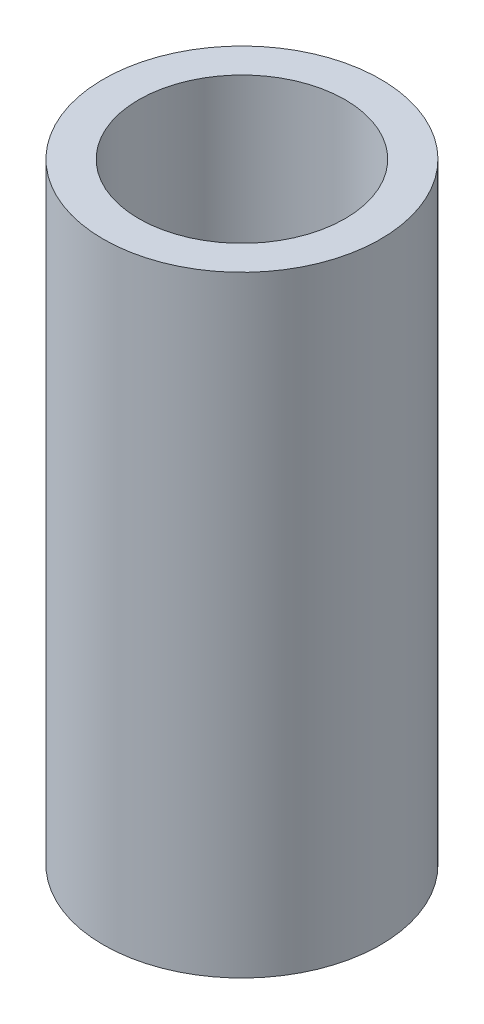
SolidWorks part; units mm, degrees
material "Nylon 101"
ref_plane "Front Plane" through (0, 0, 0) normal (0, 0, 1) x (1, 0, 0)
ref_plane "Top Plane" through (0, 0, 0) normal (0, 1, 0) x (1, 0, 0)
ref_plane "Right Plane" through (0, 0, 0) normal (1, 0, 0) x (0, 0, -1)
sketch "Sketch1" plane through (0, 0, 0) normal (0, 1, 0) x (1, 0, 0)
  circle A0 centre (0, 0) radius 1.5875
  dimension "D1" = 3.175
extrude "Boss-Extrude1" add sketch "Sketch1" along normal mid plane 7
sketch "Sketch3" plane through (0, 3.5, 0) normal (0, 1, 0) x (1, 0, 0)
  circle A0 centre (0, 0) radius 1.1811
  dimension "D1" = 2.3622
extrude "Cut-Extrude1" cut sketch "Sketch3" against normal through all
